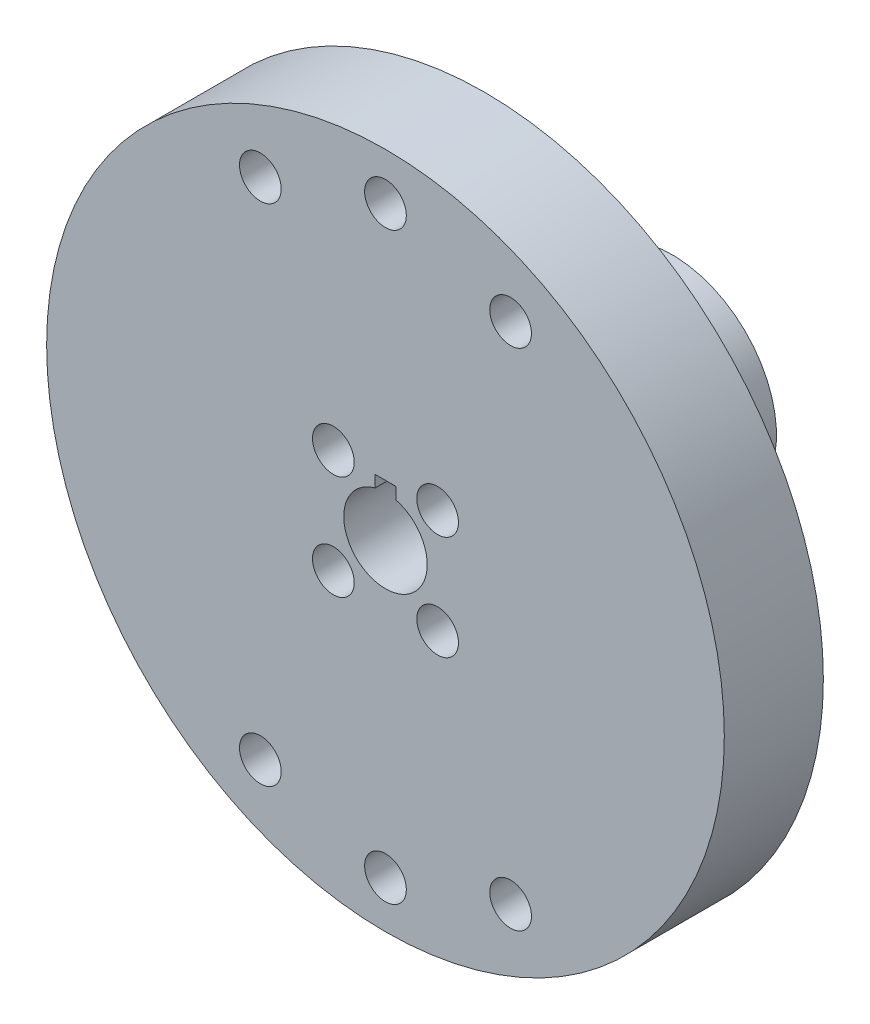
SolidWorks part; units mm, degrees
material "AISI 316 Annealed Stainless Steel Bar (SS)"
ref_plane "Front Plane" through (0, 0, 0) normal (0, 0, 1) x (1, 0, 0)
ref_plane "Top Plane" through (0, 0, 0) normal (0, 1, 0) x (1, 0, 0)
ref_plane "Right Plane" through (0, 0, 0) normal (1, 0, 0) x (0, 0, -1)
sketch "Sketch1" plane through (0, 0, 0) normal (0, 0, 1) x (1, 0, 0)
  line L0 (-1, 3.873) -> (-1, 5.003)
  line L1 (-1, 5.003) -> (1, 5.003)
  line L2 (1, 5.003) -> (1, 3.873)
  circle A0 centre (0, 0) radius 32.5
  arc A1 (-1, 3.873) -> (1, 3.873) centre (0, 0) ccw
  circle A2 centre (0, 28) radius 2
  circle A3 centre (12, 24.2) radius 2
  circle A4 centre (-12, 24.2) radius 2
  circle A5 centre (-12, -24.2) radius 2
  circle A6 centre (0, -28) radius 2
  circle A7 centre (12, -24.2) radius 2
  point P21 (0, 0)
  dimension "D1" = 8
  dimension "D2" = 65
  dimension "D7" = 4
  dimension "D10" = 4
  dimension "D11" = 4
  dimension "D3" = 1
  dimension "D4" = 2
  dimension "D5" = 1.13
  dimension "D6" = 28
  dimension "D8" = 2
  dimension "D9" = 3.8
  dimension "D12" = 12
  dimension "D13" = 12
extrude "Boss-Extrude1" add sketch "Sketch1" along normal blind 9.5
sketch "Sketch2" plane through (0, 0, 0) normal (0, 0, -1) x (-1, 0, 0)
  line L0 (0, 0) -> (17.1997, 0)
  arc A0 (-14.6097, 21.5071) -> (-14.6097, -21.5071) centre (0, 0) ccw
  arc A1 (2.1529, 25.9107) -> (-2.1529, 25.9107) centre (0, 28) ccw
  arc A2 (-8.2768, 24.6474) -> (-14.6097, 21.5071) centre (-12, 24.2) ccw
  arc A3 (14.6097, 21.5071) -> (8.2768, 24.6474) centre (12, 24.2) ccw
  arc A4 (-2.1529, 25.9107) -> (-8.2768, 24.6474) centre (0, 0) ccw
  arc A5 (8.2768, 24.6474) -> (2.1529, 25.9107) centre (0, 0) ccw
  arc A6 (14.6097, -21.5071) -> (8.2768, -24.6474) centre (12, -24.2) cw
  arc A7 (2.1529, -25.9107) -> (-2.1529, -25.9107) centre (0, -28) cw
  arc A8 (-8.2768, -24.6474) -> (-14.6097, -21.5071) centre (-12, -24.2) cw
  arc A9 (2.1529, -25.9107) -> (8.2768, -24.6474) centre (0, 0) ccw
  arc A10 (14.6097, -21.5071) -> (14.6097, 21.5071) centre (0, 0) ccw
  arc A11 (-8.2768, -24.6474) -> (-2.1529, -25.9107) centre (0, 0) ccw
  dimension "D1" = 52
  dimension "D2" = 6
  dimension "D3" = 7.5
  dimension "D4" = 7.5
extrude "Cut-Extrude1" cut sketch "Sketch2" against normal blind 3.5
sketch "Sketch4" plane through (0, 0, 3.5) normal (0, 0, -1) x (-1, 0, 0)
  line L0 (1, 5.003) -> (1, 3.873) construction
  line L1 (-1, 3.873) -> (-1, 5.003) construction
  line L2 (-1, 5.003) -> (1, 5.003) construction
  line L3 (1, 5.003) -> (1, 3.873)
  line L4 (-1, 3.873) -> (-1, 5.003)
  line L5 (-1, 5.003) -> (1, 5.003)
  arc A0 (-1, 3.873) -> (1, 3.873) centre (0, 0) ccw construction
  arc A1 (-1, 3.873) -> (1, 3.873) centre (0, 0) ccw
  circle A2 centre (0, 0) radius 17.5
  dimension "D1" = 35
extrude "Boss-Extrude2" add sketch "Sketch4" along normal blind 4
sketch "Sketch5" plane through (0, 0, -0.5) normal (0, 0, -1) x (-1, 0, 0)
  line L0 (-1, 5.003) -> (-1, 3.873) construction
  line L1 (1, 3.873) -> (1, 5.003) construction
  line L2 (1, 5.003) -> (-1, 5.003) construction
  line L3 (-1, 5.003) -> (-1, 3.873)
  line L4 (1, 3.873) -> (1, 5.003)
  line L5 (1, 5.003) -> (-1, 5.003)
  circle A0 centre (0, 0) radius 10
  arc A1 (-1, 3.873) -> (1, 3.873) centre (0, 0) ccw construction
  arc A2 (-1, 3.873) -> (1, 3.873) centre (0, 0) ccw
  dimension "D1" = 20
extrude "Boss-Extrude4" add sketch "Sketch5" along normal blind 17.5
sketch "Sketch6" plane through (0, 0, 0) normal (1, 0, 0) x (0, 0, -1)
  line L0 (-9.5, 32.5) -> (-9.5, -32.5) construction
  circle A0 centre (6.8, 0) radius 1.225
  dimension "D1" = 2.45
  dimension "D2" = 16.3
extrude "Cut-Extrude2" cut sketch "Sketch6" against normal mid plane 40
hole_wizard "Ø4.0mm Dowel Hole1" positions "Sketch8" profile "Sketch9" hole size "Ø4.0" standard "ANSI Metric" end condition through all
sketch "Sketch8" plane through (0, 0, -18) normal (0, 0, -1) x (-1, 0, 0)
  point P0 (5, 5)
  dimension "D1" = 5
  dimension "D2" = 5
sketch "Sketch9" plane through (-5, 5, -18) normal (1, 0, 0) x (0, 1, 0)
  line L0 (0, 0) -> (0, 27.5)
  line L1 (0, 27.5) -> (2, 27.5)
  line L2 (2, 27.5) -> (2, 0)
  line L5 (2, 0) -> (0, 0)
  line L11 (0, -6.35) -> (0, 107.95) construction
  dimension "Thru Hole Dia." = 4
  dimension "Thru Hole Depth" = 27.5
pattern_circular "CirPattern1" count 4 over 360 about axis through (0, 0, 0) along (0, 0, 1) of "Ø4.0mm Dowel Hole1"
fillet "Fillet1" radius 1 1 edges at (-10, 0, -0.5)
